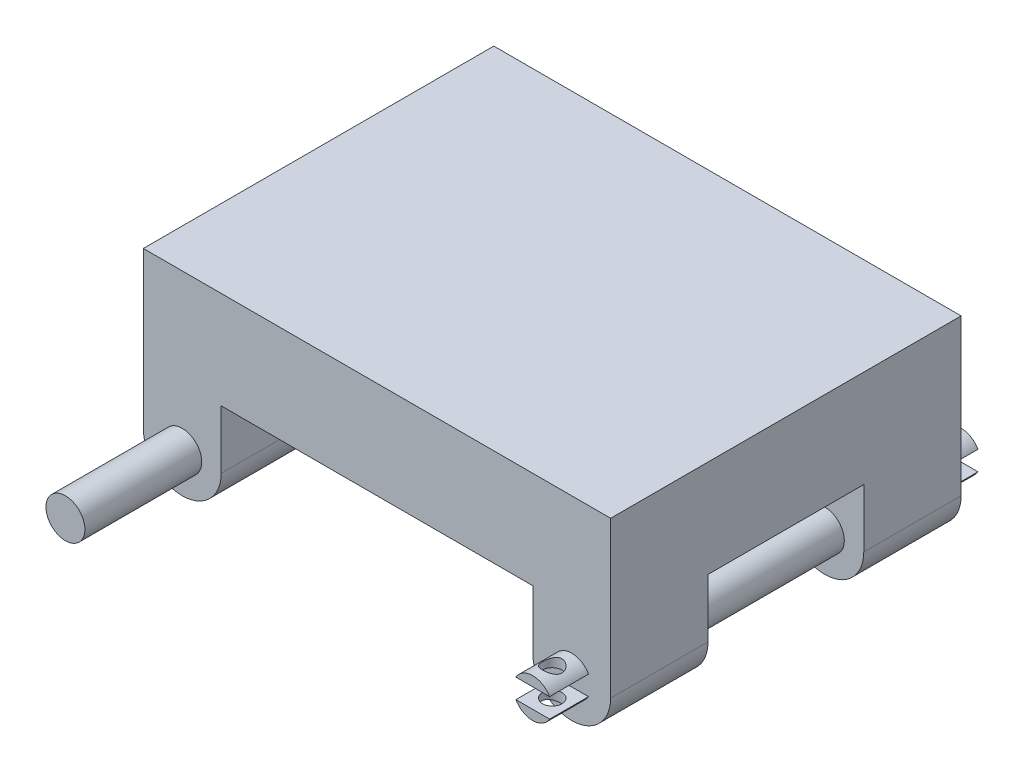
SolidWorks part; units mm, degrees
ref_plane "Front Plane" through (0, 0, 0) normal (0, 0, 1) x (1, 0, 0)
ref_plane "Top Plane" through (0, 0, 0) normal (0, 1, 0) x (1, 0, 0)
ref_plane "Right Plane" through (0, 0, 0) normal (1, 0, 0) x (0, 0, -1)
sketch "Sketch1" plane through (0, 0, 0) normal (0, 1, 0) x (1, 0, 0)
  line L1 (304.8, 228.6) -> (-304.8, 228.6)
  line L2 (304.8, 228.6) -> (304.8, -228.6)
  line L3 (304.8, -228.6) -> (-304.8, -228.6)
  line L4 (-304.8, 228.6) -> (-304.8, -228.6)
  line L5 (304.8, 228.6) -> (-304.8, -228.6) construction
  line L6 (304.8, -228.6) -> (-304.8, 228.6) construction
  point P0 (0, 0)
  dimension "D1" = 609.6
  dimension "D2" = 457.2
extrude "Boss-Extrude1" add sketch "Sketch1" along normal blind 127 contours L2 L1 L4 L3
sketch "Sketch2" plane through (0, 0, 228.6) normal (0, 0, 1) x (1, 0, 0)
  line L0 (304.8, 0) -> (304.8, -76.2)
  line L1 (203.2, 0) -> (203.2, -76.2)
  line L2 (304.8, 0) -> (-304.8, 0) construction
  line L3 (-304.8, 0) -> (-304.8, -76.2)
  line L4 (-203.2, 0) -> (-203.2, -76.2)
  circle A0 centre (254, -76.2) radius 50.8
  circle A2 centre (-254, -76.2) radius 50.8
  circle A3 centre (-254, -76.2) radius 25.4
  circle A4 centre (254, -76.2) radius 25.4
  line M5 (-304.8, 0) -> (304.8, 0)
  dimension "D3" = 101.6
  dimension "D1" = 76.2
  dimension "D2" = 101.6
  dimension "D4" = 50.8
  dimension "D5" = 2
extrude "Boss-Extrude2" add sketch "Sketch2" against normal blind 127 contours A2 L4 L3 M5 | A2 A3 | A0 A4 | A0 L0 L1 M5
sketch "Sketch3" plane through (0, 0, -228.6) normal (0, 0, -1) x (-1, 0, 0)
  line L0 (304.8, 0) -> (304.8, -76.2) construction
  line L1 (203.2, 0) -> (203.2, -76.2) construction
  line L2 (-203.2, 0) -> (-203.2, -76.2) construction
  line L3 (-304.8, 0) -> (-304.8, -76.2) construction
  line L4 (304.8, 0) -> (304.8, -76.2)
  line L5 (203.2, 0) -> (203.2, -76.2)
  line L6 (-203.2, 0) -> (-203.2, -76.2)
  line L7 (-304.8, 0) -> (-304.8, -76.2)
  circle A0 centre (254, -76.2) radius 25.4 construction
  arc A1 (203.2, -76.2) -> (304.8, -76.2) centre (254, -76.2) ccw construction
  circle A2 centre (-254, -76.2) radius 25.4 construction
  arc A3 (-304.8, -76.2) -> (-203.2, -76.2) centre (-254, -76.2) ccw construction
  circle A4 centre (254, -76.2) radius 25.4
  arc A5 (203.2, -76.2) -> (304.8, -76.2) centre (254, -76.2) ccw
  circle A6 centre (-254, -76.2) radius 25.4
  arc A7 (-304.8, -76.2) -> (-203.2, -76.2) centre (-254, -76.2) ccw
  line M1 (-304.8, 0) -> (304.8, 0)
extrude "Boss-Extrude3" add sketch "Sketch3" against normal blind 127 contours L7 A7 L6 A6 M1 | L5 A5 L4 A4 M1
sketch "Sketch5" plane through (0, 0, 228.6) normal (0, 0, 1) x (1, 0, 0)
  circle A0 centre (254, -76.2) radius 25.4 construction
  circle A1 centre (-254, -76.2) radius 25.4 construction
  circle A2 centre (254, -76.2) radius 25.4
  circle A3 centre (-254, -76.2) radius 25.4
extrude "Boss-Extrude4" add sketch "Sketch5" along normal blind 50.8 and the other way blind 508 contours A3 | A2
sketch "Sketch6" plane through (0, 127, 0) normal (0, 1, 0) x (1, 0, 0)
  circle A0 centre (254, -254) radius 12.7
  circle A1 centre (254, 254) radius 12.7
  dimension "D1" = 254
  dimension "D5" = 25.4
  dimension "D6" = 25.4
  dimension "D2" = 254
  dimension "D3" = 254
  dimension "D4" = 254
extrude "Cut-Extrude1" cut sketch "Sketch6" against normal through all
sketch "Sketch7" plane through (304.8, 0, 0) normal (1, 0, 0) x (0, 0, -1)
  line L0 (-228.6, -50.8) -> (-279.4, -50.8) construction
  line L1 (-279.4, -101.6) -> (-228.6, -101.6) construction
  line L2 (-279.4, -101.6) -> (-266.7, -101.6) construction
  line L3 (-266.7, -50.8) -> (-279.4, -50.8) construction
  line L4 (-228.6, -50.8) -> (-279.4, -50.8)
  line L5 (-279.4, -101.6) -> (-228.6, -101.6)
  line L6 (-279.4, -101.6) -> (-266.7, -101.6)
  line L7 (-266.7, -50.8) -> (-279.4, -50.8)
  line L8 (228.6, -101.6) -> (279.4, -101.6) construction
  line L9 (266.7, -101.6) -> (279.4, -101.6) construction
  line L10 (279.4, -50.8) -> (228.6, -50.8) construction
  line L11 (241.3, -50.8) -> (228.6, -50.8) construction
  line L12 (228.6, -101.6) -> (279.4, -101.6)
  line L13 (266.7, -101.6) -> (279.4, -101.6)
  line L14 (279.4, -50.8) -> (228.6, -50.8)
  line L15 (241.3, -50.8) -> (228.6, -50.8)
  line L16 (-279.4, -50.8) -> (-279.4, -101.6) construction
  line L17 (-330.2, -63.5) -> (-228.6, -63.5)
  line L18 (-330.2, -63.5) -> (-330.2, -88.9)
  line L19 (-330.2, -88.9) -> (-228.6, -88.9)
  line L20 (-228.6, -63.5) -> (-228.6, -88.9)
  line L21 (-330.2, -63.5) -> (-228.6, -88.9) construction
  line L22 (-330.2, -88.9) -> (-228.6, -63.5) construction
  line L23 (-228.6, -50.8) -> (-228.6, -101.6) construction
  line L24 (279.4, -101.6) -> (279.4, -50.8) construction
  line L25 (279.4, -63.5) -> (228.6, -63.5)
  line L26 (279.4, -63.5) -> (279.4, -88.9)
  line L27 (279.4, -88.9) -> (228.6, -88.9)
  line L28 (228.6, -63.5) -> (228.6, -88.9)
  line L29 (228.6, -127) -> (228.6, -76.2) construction
  point P9 (-279.4, -76.2)
  line M8 (228.6, -76.2) -> (228.6, 127)
  line M10 (-228.6, 127) -> (-228.6, -76.2)
  dimension "D1" = 25.4
  dimension "D2" = 25.4
extrude "Cut-Extrude2" cut sketch "Sketch7" against normal blind 101.6 contours L20 L17 L18 L19 M10 | L28 L27 L26 L25 M8
sketch "Sketch8" plane through (0, 0, -279.4) normal (0, 0, -1) x (-1, 0, 0)
  circle A0 centre (254, -76.2) radius 25.4 construction
  circle A1 centre (254, -76.2) radius 25.4
extrude "Boss-Extrude5" add sketch "Sketch8" along normal blind 101.6
sketch "Sketch9" plane through (0, 0, 279.4) normal (0, 0, 1) x (1, 0, 0)
  circle A0 centre (-254, -76.2) radius 25.4 construction
  circle A1 centre (-254, -76.2) radius 25.4
extrude "Boss-Extrude6" add sketch "Sketch9" along normal blind 101.6
